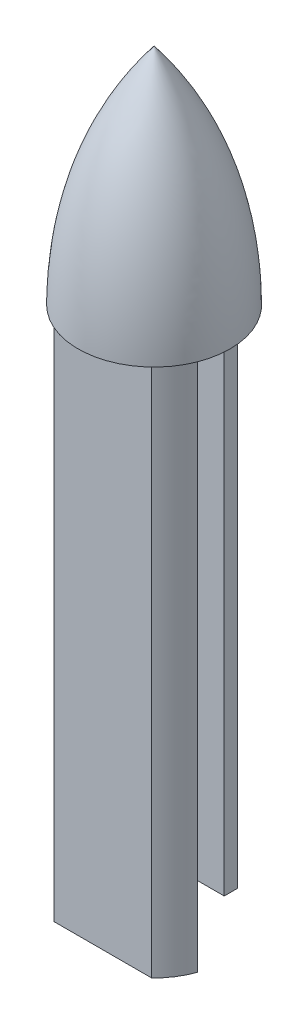
SolidWorks part; units mm, degrees
ref_plane "Front Plane" through (0, 0, 0) normal (0, 0, 1) x (1, 0, 0)
ref_plane "Top Plane" through (0, 0, 0) normal (0, 1, 0) x (1, 0, 0)
ref_plane "Right Plane" through (0, 0, 0) normal (1, 0, 0) x (0, 0, -1)
sketch "Sketch1" plane through (0, 0, 0) normal (0, 1, 0) x (1, 0, 0)
  circle A0 centre (0, 0) radius 27.1
  dimension "D1" = 54.2
sketch "Sketch2" plane through (0, 0, 0) normal (0, 0, 1) x (1, 0, 0)
  line L0 (0, 0) -> (0, 80)
  line L1 (27.1, 0) -> (-27.1, 0) construction
  line L2 (0, 0) -> (27.1, 0)
  spline S0 degree 2 poles (0, 80) (26.8413, 45.5817) (27.1, 0) knots 0 0 0 1 1 1
  dimension "D1" = 80
  dimension "D2" = 27.1
revolve "Revolve1" add sketch "Sketch2" angle 360 about L0
sketch "Sketch3" plane through (0, 0, 0) normal (0, -1, 0) x (1, 0, 0)
  circle A0 centre (0, 0) radius 25.2
  dimension "D1" = 50.4
extrude "Boss-Extrude1" add sketch "Sketch3" along normal blind 190
sketch "Sketch4" plane through (0, -190, 0) normal (0, -1, 0) x (1, 0, 0)
  line L0 (0, 0) -> (0, -32.2934) construction
  line L1 (23.8113, -8.25) -> (-23.8113, -8.25)
  line L3 (23.8113, 8.25) -> (-23.8113, 8.25)
  line L7 (-5, -20) -> (5, -20)
  line L8 (-5, -20) -> (-5, -30.1395)
  line L9 (-5, -30.1395) -> (5, -30.1395)
  line L10 (5, -20) -> (5, -30.1395)
  line L11 (-17.3775, 18.25) -> (17.3775, 18.25)
  circle A0 centre (0, 0) radius 25.2 construction
  circle A1 centre (0, 0) radius 25.2
  point P0 (0, 0)
  point P13 (0, -20)
  point P22 (0, 0)
  circle M13 centre (0, 0) radius 25.2
  dimension "D6" = 50.4
  dimension "D4" = 10
  dimension "D3" = 20
  dimension "D5" = 10
  dimension "D1" = 8.25
  dimension "D2" = 8.25
extrude "Cut-Extrude1" cut sketch "Sketch4" against normal up to surface (190 mm away) contours L0 L11 M13 | L0 A1 L11 | L3 L0 L1 M13 | L0 L3 L1 M13 | L0 L1 L8 L7 M13 | L1 L0 L7 L10 M13 up to face at (0, 0, -25.2)
sketch "Sketch5" plane through (0, 0, 0) normal (0, -1, 0) x (1, 0, 0)
  line L1 (-15, 1.7313) -> (15, 1.7313)
  line L2 (-15, 1.7313) -> (-15, 31.8824)
  line L3 (-15, 31.8824) -> (15, 31.8824)
  line L4 (15, 1.7313) -> (15, 31.8824)
  line L5 (0, 0) -> (0, 14.0488) construction
  line L6 (0, 0) -> (-28.0397, 28.0397)
  line L7 (0, 0) -> (27.4797, 27.4797)
  line L8 (11.5, 26.7313) -> (-11.5, 26.7313)
  circle A0 centre (0, 0) radius 27.1
  circle A1 centre (0, 0) radius 29.1
  circle A3 centre (0, 0) radius 25.2
  point P12 (0, 31.8824)
  dimension "D2" = 54.2
  dimension "D3" = 50.4
  dimension "D1" = 2
  dimension "D4" = 30
  dimension "D5" = 45
  dimension "D6" = 23
  dimension "D7" = 25
equation "\"TubeOutsideDiameter\"= 52"
equation "\"TubeInnerDiameter\"= 47.8"
equation "\"ReleaseMechanisumHeight\"=100"
equation "\"WireDiameter\"=3.38983"
equation "\"servoHoleDiameter\"= 2.8"
equation "\"CordDiameter\"= 5"
equation "\"MountingBoldDiameter\"=2.8"
equation "\"TubeMountingBoltDiameter\"= 5"
equation "\"CardTubeOutsideDiameter\"= 54.2"
equation "\"CardTubeInsideDiameter\"= 50.4"
equation "\"D1@Sketch1\"=\"CardTubeOutsideDiameter\""
equation "\"D1@Sketch3\"=\"CardTubeInsideDiameter\""
equation "\"D6@Sketch4\"=\"CardTubeInsideDiameter\""
equation "\"D1@Sketch4\"=16.5/2"
equation "\"D2@Sketch5\"=\"CardTubeOutsideDiameter\""
equation "\"D2@Sketch2\"=\"CardTubeOutsideDiameter\"/2"
equation "\"D3@Sketch5\"=\"CardTubeInsideDiameter\""
